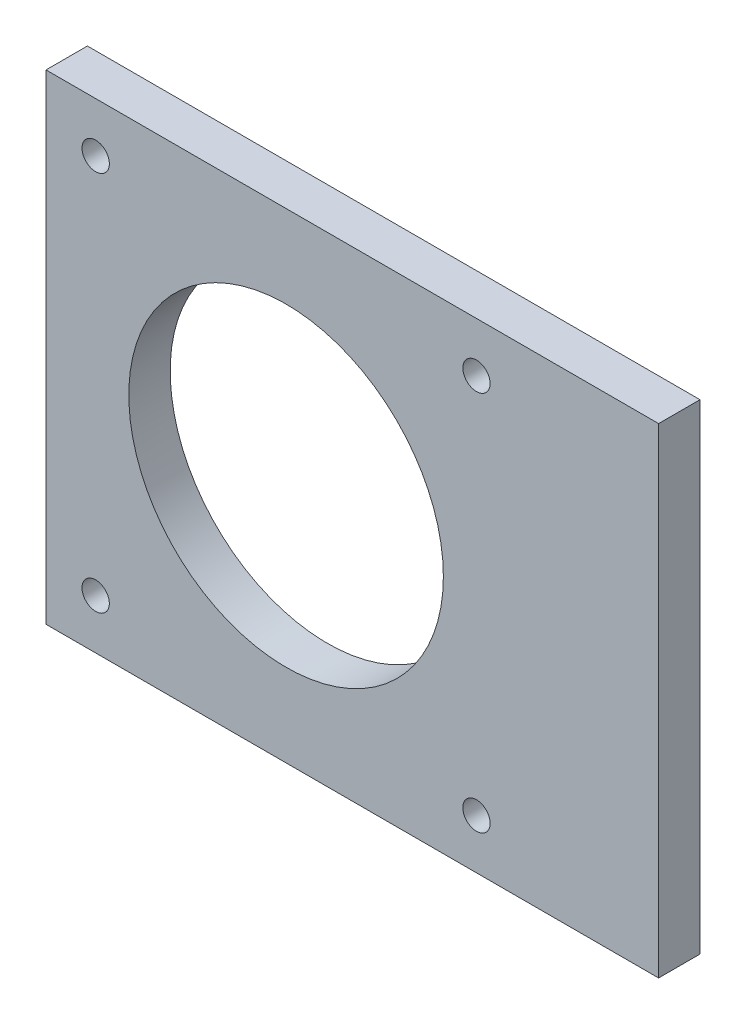
SolidWorks part; units mm, degrees
ref_plane "前视基准面" through (0, 0, 0) normal (0, 0, 1) x (1, 0, 0)
ref_plane "上视基准面" through (0, 0, 0) normal (0, 1, 0) x (1, 0, 0)
ref_plane "右视基准面" through (0, 0, 0) normal (1, 0, 0) x (0, 0, -1)
sketch "草图1" plane through (0, 0, 0) normal (0, 0, 1) x (1, 0, 0)
  line L0 (29, 29) -> (45, 29)
  line L1 (-29, 29) -> (29, 29)
  line L2 (-29, 29) -> (-29, -29)
  line L3 (-29, -29) -> (29, -29)
  line L4 (45, 29) -> (45, -29)
  line L5 (-29, 29) -> (29, -29) construction
  line L6 (-29, -29) -> (29, 29) construction
  line L7 (45, -29) -> (29, -29)
  circle A0 centre (-23, 23) radius 2 construction
  circle A1 centre (23, 23) radius 2 construction
  point P0 (0, 0)
  dimension "D3" = 6
  dimension "D4" = 16
  dimension "D1" = 58
  dimension "D2" = 58
extrude "凸台-拉伸1" add sketch "草图1" along normal blind 5
sketch "草图3" plane through (0, 0, 5) normal (0, 0, 1) x (1, 0, 0)
  line L0 (-29, 29) -> (-29, -29) construction
  line L1 (45, 29) -> (-29, 29) construction
  line L3 (29, -1000.0808) -> (29, 48999.9192) construction
  line L4 (-29, 29) -> (-29, -29) construction
  circle A0 centre (-23, 23) radius 2
  circle A1 centre (23, 23) radius 2
  dimension "D1" = 6
  dimension "D2" = 6
  dimension "D3" = 6
  dimension "D4" = 58
  dimension "D5" = 6
hole_wizard "M4 螺纹孔的螺纹孔钻头1" positions "3D草图2" profile "草图4" hole size "M4" standard "GB" end condition through all
sketch3d "3D草图2"
  point P0 (-23, 23, 5)
  point P3 (23, 23, 5)
sketch "草图4" plane through (-23, 23, 5) normal (1, 0, 0) x (0, -1, 0)
  line L0 (0, 0) -> (0, 5)
  line L1 (0, 5) -> (1.65, 5)
  line L2 (1.65, 5) -> (1.65, 0)
  line L5 (1.65, 0) -> (0, 0)
  line L11 (0, -6.35) -> (0, 107.95) construction
  dimension "通孔孔直径" = 3.3
  dimension "通孔孔深度" = 5
mirror "镜向1" about plane through (0, 0, 0) normal (0, 1, 0) of "M4 螺纹孔的螺纹孔钻头1"
sketch "草图5" plane through (0, 0, 5) normal (0, 0, 1) x (1, 0, 0)
  circle A0 centre (0, 0) radius 19
extrude "切除-拉伸1" cut sketch "草图5" against normal through all
